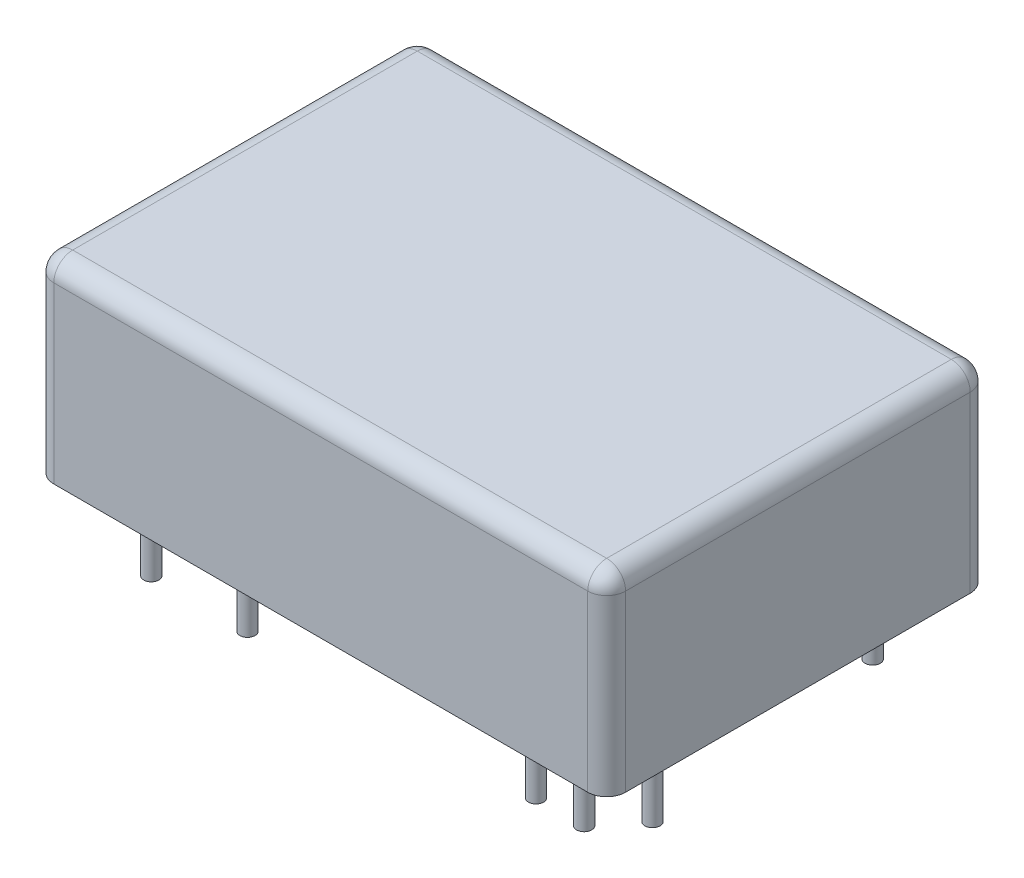
SolidWorks part; units mm, degrees
ref_plane "Спереди" through (0, 0, 0) normal (0, 0, 1) x (1, 0, 0)
ref_plane "Сверху" through (0, 0, 0) normal (0, 1, 0) x (1, 0, 0)
ref_plane "Справа" through (0, 0, 0) normal (1, 0, 0) x (0, 0, -1)
sketch "Эскиз1" plane through (0, 0, 0) normal (0, 1, 0) x (1, 0, 0)
  line L1 (-15.1, 10.1) -> (15.1, 10.1)
  line L2 (-15.1, 10.1) -> (-15.1, -10.1)
  line L3 (-15.1, -10.1) -> (15.1, -10.1)
  line L4 (15.1, 10.1) -> (15.1, -10.1)
  line L5 (-15.1, 10.1) -> (15.1, -10.1) construction
  line L6 (-15.1, -10.1) -> (15.1, 10.1) construction
  point P0 (0, 0)
  dimension "D1" = 30.2
  dimension "D2" = 20.2
extrude "Бобышка-Вытянуть1" add sketch "Эскиз1" along normal blind 10.2
fillet "Скругление1" radius 1 8 edges at (0, 10.2, 10.1) (-15.1, 10.2, 0) (0, 10.2, -10.1) (15.1, 10.2, 0) (-15.1, 5.1, 10.1) (-15.1, 5.1, -10.1) (15.1, 5.1, -10.1) (15.1, 5.1, 10.1)
sketch "Эскиз2" plane through (0, 0, 0) normal (0, -1, 0) x (1, 0, 0)
  line L0 (13.15, 7.72) -> (13.15, -7.52) construction
  line L1 (13.15, -7.52) -> (-11.33, -7.52) construction
  line L2 (-11.33, 7.72) -> (13.15, 7.72) construction
  line L3 (11.53, 7.72) -> (11.53, -7.52) construction
  line L4 (8.99, 7.72) -> (8.99, -7.52) construction
  line L5 (6.45, 7.72) -> (6.45, -7.52) construction
  line L6 (-6.25, 7.72) -> (-6.25, -7.52) construction
  line L7 (-11.33, 7.72) -> (-11.33, -7.52) construction
  line L8 (-14.1, 10.1) -> (14.1, 10.1) construction
  circle A0 centre (11.53, 7.72) radius 0.4
  circle A1 centre (13.15, 5.73) radius 0.4
  circle A2 centre (8.99, 7.72) radius 0.4
  circle A3 centre (6.45, -7.52) radius 0.4
  circle A4 centre (-6.25, 7.72) radius 0.4
  circle A5 centre (-11.33, 7.72) radius 0.4
  circle A6 centre (-11.33, -7.52) radius 0.4
  circle A7 centre (-6.25, -7.52) radius 0.4
  circle A9 centre (8.99, -7.52) radius 0.4
  circle A10 centre (11.53, -7.52) radius 0.4
  point P23 (13.15, 5.73)
  dimension "D1" = 2.38
  dimension "D2" = 17.62
  dimension "D4" = 2.54
  dimension "D5" = 2.54
  dimension "D6" = 17.78
  dimension "D7" = 22.86
  dimension "D8" = 1.62
extrude "Бобышка-Вытянуть3" add sketch "Эскиз2" along normal blind 4
